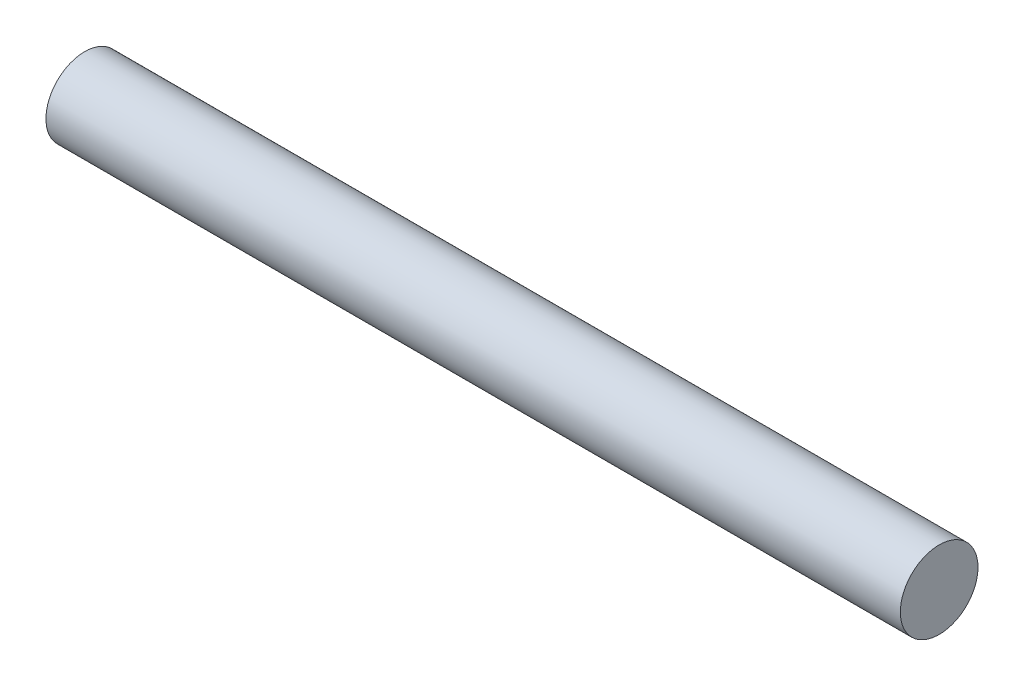
SolidWorks part; units mm, degrees
ref_plane "Front Plane" through (0, 0, 0) normal (0, 0, 1) x (1, 0, 0)
ref_plane "Top Plane" through (0, 0, 0) normal (0, 1, 0) x (1, 0, 0)
ref_plane "Right Plane" through (0, 0, 0) normal (1, 0, 0) x (0, 0, -1)
sketch "Sketch1" plane through (0, 0, 0) normal (1, 0, 0) x (0, 0, -1)
  circle A0 centre (0, 0) radius 1
  dimension "D1" = 2
extrude "Boss-Extrude1" add sketch "Sketch1" along normal blind 22
